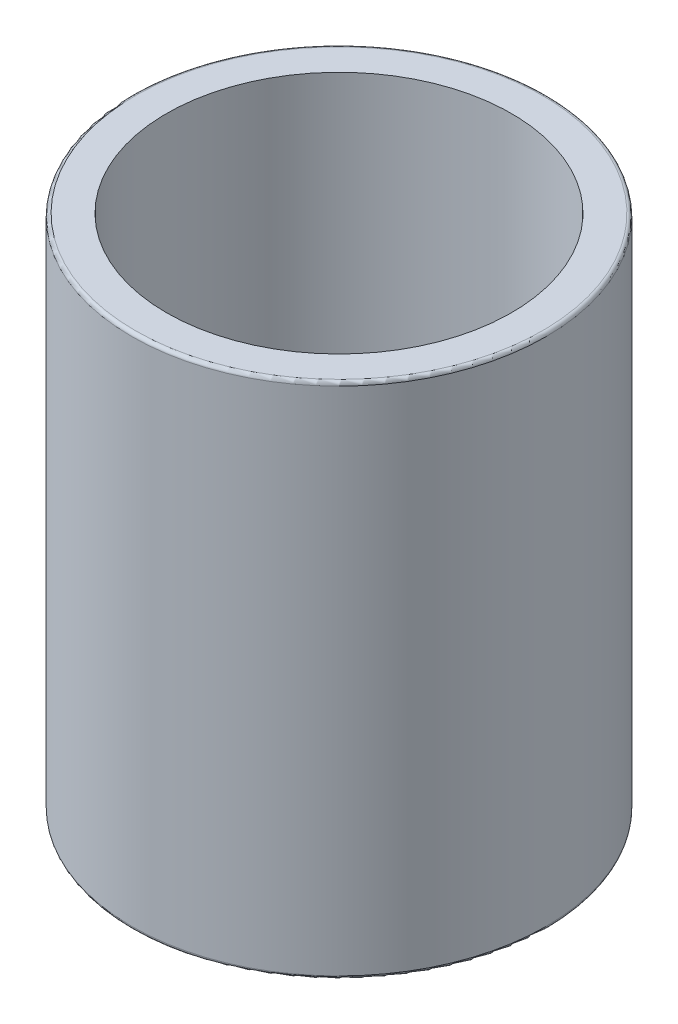
SolidWorks part; units mm, degrees
material "ABS"
ref_plane "Ebene vorne" through (0, 0, 0) normal (0, 0, 1) x (1, 0, 0)
ref_plane "Ebene oben" through (0, 0, 0) normal (0, 1, 0) x (1, 0, 0)
ref_plane "Ebene rechts" through (0, 0, 0) normal (1, 0, 0) x (0, 0, -1)
sketch "Skizze1" plane through (0, 0, 0) normal (0, 1, 0) x (1, 0, 0)
  circle A0 centre (0, 0) radius 5
  circle A1 centre (0, 0) radius 6
  dimension "D1" = 10
  dimension "D2" = 1
extrude "Aufsatz-Linear austragen1" add sketch "Skizze1" along normal mid plane 15
fillet "Verrundung1" radius 0.1 2 edges at (0, -7.5, 6) (0, 7.5, 6)
